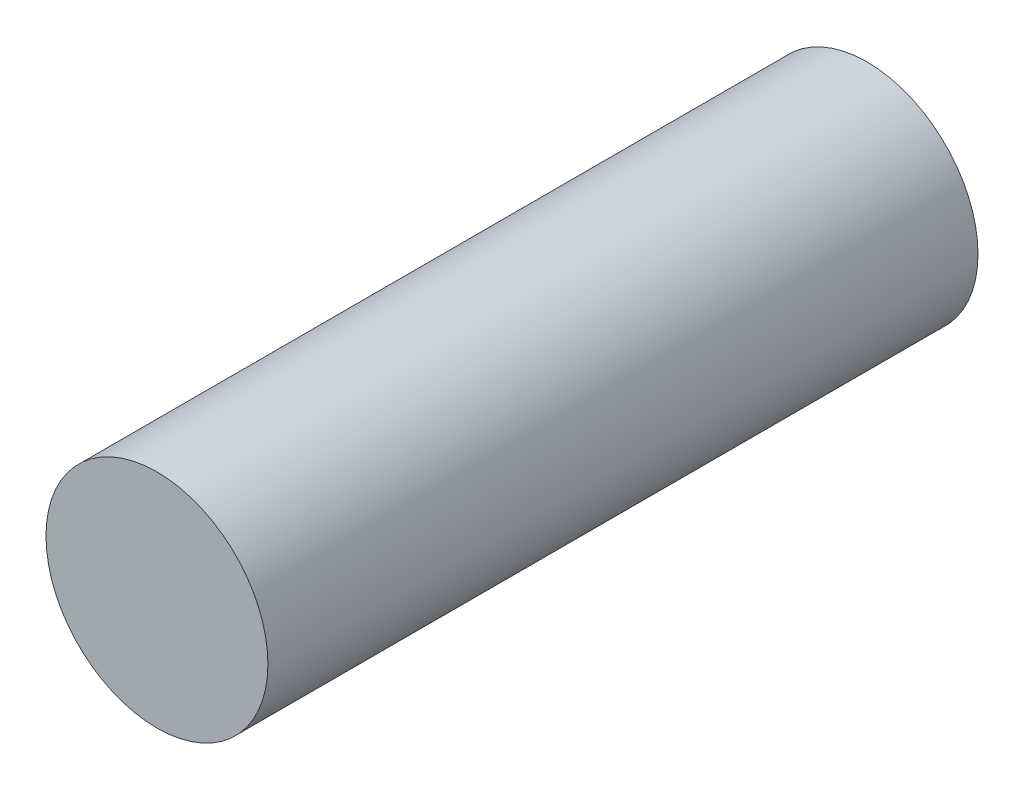
SolidWorks part; units mm, degrees
ref_plane "Piano frontale" through (0, 0, 0) normal (0, 0, 1) x (1, 0, 0)
ref_plane "Piano superiore" through (0, 0, 0) normal (0, 1, 0) x (1, 0, 0)
ref_plane "Piano destro" through (0, 0, 0) normal (1, 0, 0) x (0, 0, -1)
sketch "Schizzo1" plane through (0, 0, 0) normal (0, 0, 1) x (1, 0, 0)
  circle A0 centre (0, 0) radius 3.75
extrude "Estrusione-Estrusione1" add sketch "Schizzo1" against normal blind 24
